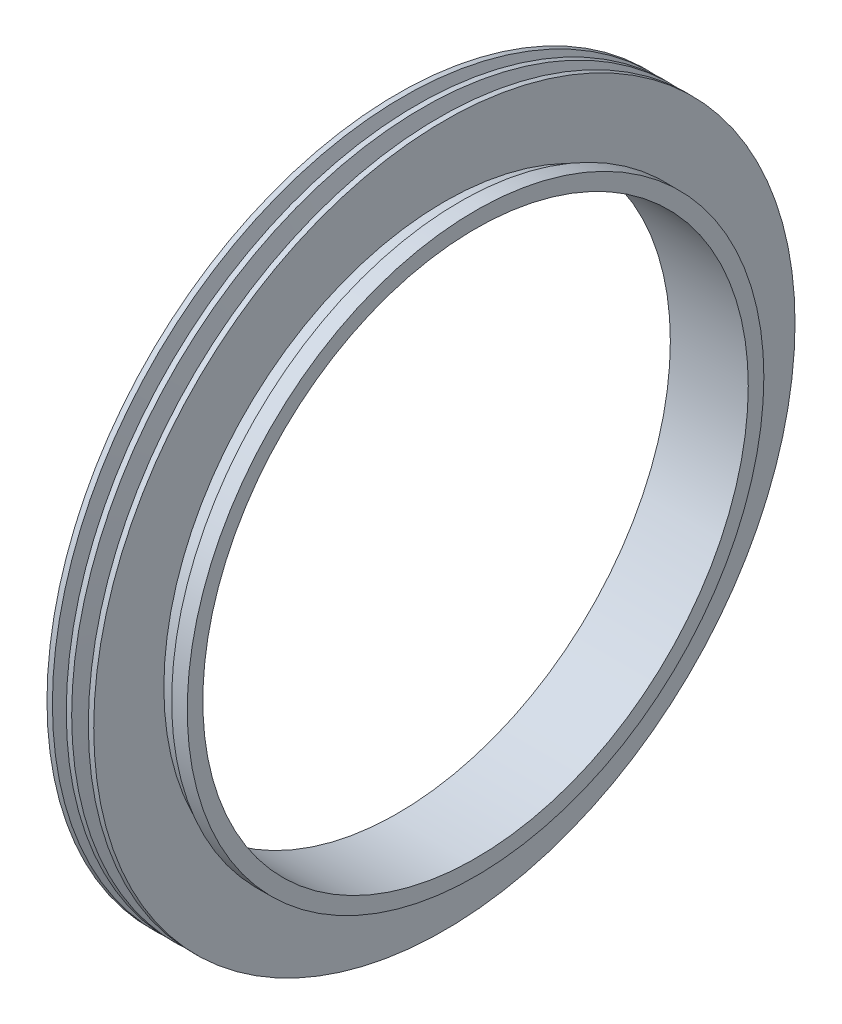
SolidWorks part; units mm, degrees
ref_plane "Płaszczyzna przednia" through (0, 0, 0) normal (0, 0, 1) x (1, 0, 0)
ref_plane "Płaszczyzna górna" through (0, 0, 0) normal (0, 1, 0) x (1, 0, 0)
ref_plane "Płaszczyzna prawa" through (0, 0, 0) normal (1, 0, 0) x (0, 0, -1)
sketch "Szkic1" plane through (0, 0, 0) normal (0, 0, 1) x (1, 0, 0)
  line L0 (0, 17.5) -> (-5, 17.5)
  line L1 (0, 17.5) -> (0, 18.5)
  line L2 (0, 18.5) -> (-1, 18.5)
  line L3 (-1, 18.5) -> (-1, 18)
  line L4 (-1, 18) -> (-2, 18)
  line L5 (-2, 18) -> (-2, 22.5)
  line L6 (-2, 22.5) -> (-2.3474, 22.5)
  line L7 (-2.3474, 22.5) -> (-2.8993, 20.9116)
  line L8 (-2.8993, 20.9116) -> (-3.1016, 20.9116)
  line L9 (-3.1016, 20.9116) -> (-3.4155, 22.5)
  line L10 (-3.4155, 22.5) -> (-3.763, 22.5)
  line L11 (-3.763, 22.5) -> (-4.0817, 20.9116)
  line L12 (-5, 17.5) -> (-5, 22.5)
  line L13 (-5, 22.5) -> (-4.6526, 22.5)
  line L15 (-4.0817, 20.9116) -> (-4.284, 20.9116)
  line L16 (-4.284, 20.9116) -> (-4.6526, 22.5)
  line L17 (0, 0) -> (-5.5314, 0)
  dimension "D1" = 1
  dimension "D2" = 1
  dimension "D3" = 1
  dimension "D4" = 0.5
  dimension "D5" = 4.5
  dimension "D6" = 5
  dimension "D7" = 5
  dimension "D8" = 17.5
revolve "Obrót1" add sketch "Szkic1" angle 360 about L17
